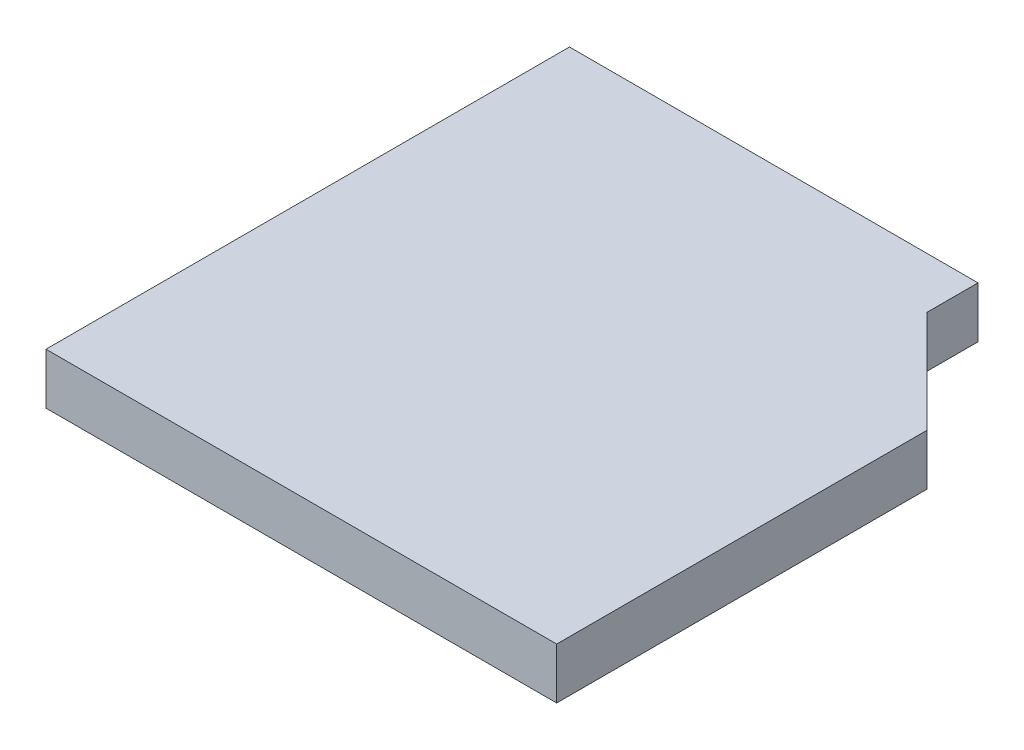
SolidWorks part; units mm, degrees
ref_plane "Front Plane" through (0, 0, 0) normal (0, 0, 1) x (1, 0, 0)
ref_plane "Top Plane" through (0, 0, 0) normal (0, 1, 0) x (1, 0, 0)
ref_plane "Right Plane" through (0, 0, 0) normal (1, 0, 0) x (0, 0, -1)
sketch "Sketch1" plane through (0, 0, 0) normal (0, 1, 0) x (1, 0, 0)
  line L1 (0, 0) -> (127, 0)
  line L2 (0, 0) -> (0, 130.175)
  line L3 (0, 130.175) -> (101.6, 130.175)
  line L4 (127, 0) -> (127, 92.075)
  line L5 (101.6, 130.175) -> (101.6, 117.475)
  line L6 (101.6, 117.475) -> (127, 92.075)
  dimension "D1" = 130.175
  dimension "D2" = 127
  dimension "D3" = 12.7
  dimension "D4" = 45
  dimension "D5" = 25.4
extrude "Boss-Extrude1" add sketch "Sketch1" along normal blind 12.7
